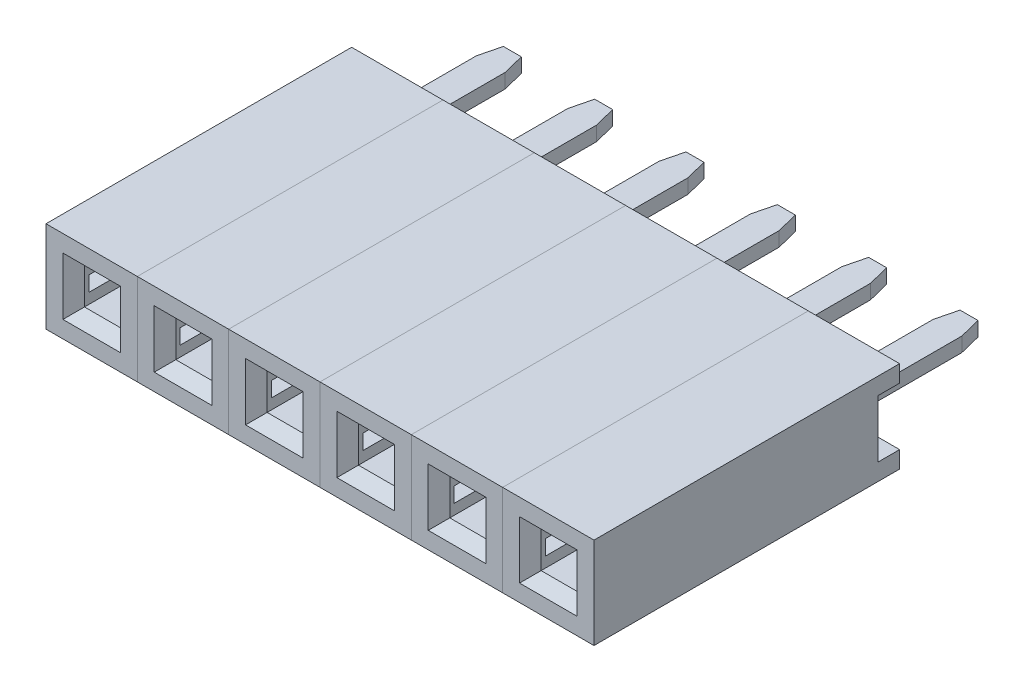
SolidWorks part; units mm, degrees
ref_plane "Спереди" through (0, 0, 0) normal (0, 0, 1) x (1, 0, 0)
ref_plane "Сверху" through (0, 0, 0) normal (0, 1, 0) x (1, 0, 0)
ref_plane "Справа" through (0, 0, 0) normal (1, 0, 0) x (0, 0, -1)
sketch "Эскиз1" plane through (0, 0, 0) normal (0, 0, 1) x (1, 0, 0)
  line L0 (0, 1.27) -> (0, 0) construction
  line L1 (1.27, 2.54) -> (-1.27, 2.54)
  line L2 (1.27, 2.54) -> (1.27, 0)
  line L3 (1.27, 0) -> (-1.27, 0)
  line L4 (-1.27, 2.54) -> (-1.27, 0)
  line L5 (1.27, 2.54) -> (-1.27, 0) construction
  line L6 (1.27, 0) -> (-1.27, 2.54) construction
  dimension "D1" = 2.54
extrude "Бобышка-Вытянуть1" add sketch "Эскиз1" along normal blind 8.5
sketch "Эскиз2" plane through (0, 0, 0) normal (0, 0, -1) x (-1, 0, 0)
  line L0 (0, 1.27) -> (0, 0) construction
  line L1 (1, 1.48) -> (-1, 1.48)
  line L2 (1, 1.48) -> (1, 1.06)
  line L3 (1, 1.06) -> (-1, 1.06)
  line L4 (-1, 1.48) -> (-1, 1.06)
  line L5 (1, 1.48) -> (-1, 1.06) construction
  line L6 (1, 1.06) -> (-1, 1.48) construction
  line L7 (0, 1.27) -> (-1.27, 1.27) construction
  line L8 (-1.27, 0) -> (-1.27, 2.54) construction
  point P0 (0, 1.27)
  dimension "D1" = 2
  dimension "D2" = 0.42
extrude "Вырез-Вытянуть1" cut sketch "Эскиз2" against normal offset from surface (8.08 mm away) 0.42 up to face at (0, 1.27, 8.5)
sketch "Эскиз3" plane through (0, 0, 8.5) normal (0, 0, 1) x (1, 0, 0)
  line L0 (0, 1.27) -> (-1.27, 1.27) construction
  line L1 (-0.5, 0.77) -> (0.5, 0.77)
  line L2 (-0.5, 0.77) -> (-0.5, 1.77)
  line L3 (-0.5, 1.77) -> (0.5, 1.77)
  line L4 (0.5, 0.77) -> (0.5, 1.77)
  line L5 (-0.5, 0.77) -> (0.5, 1.77) construction
  line L6 (-0.5, 1.77) -> (0.5, 0.77) construction
  line L7 (-1.27, 2.54) -> (-1.27, 0) construction
  line L8 (0, 1.27) -> (0, 0) construction
  line L9 (-1.27, 0) -> (1.27, 0) construction
  point P0 (0, 1.27)
  dimension "D1" = 1
  dimension "D2" = 1
extrude "Вырез-Вытянуть2" cut sketch "Эскиз3" against normal offset from surface (6.5 mm away) 2 up to face at (0, 1.27, 0)
sketch "Эскиз4" plane through (-1.27, 0, 0) normal (-1, 0, 0) x (0, 0, 1)
  line L0 (0, 2.54) -> (0, 0) construction
  line L1 (0.6, 0.47) -> (0, 0.47)
  line L2 (0.6, 0.47) -> (0.6, 2.07)
  line L3 (0.6, 2.07) -> (0, 2.07)
  line L4 (0, 0.47) -> (0, 2.07)
  line L5 (0.6, 0.47) -> (0, 2.07) construction
  line L6 (0.6, 2.07) -> (0, 0.47) construction
  line L7 (0.3, 1.27) -> (0, 1.27) construction
  point P0 (0.3, 1.27)
  dimension "D1" = 0.6
  dimension "D2" = 1.6
extrude "Вырез-Вытянуть3" cut sketch "Эскиз4" against normal through all
ref_plane "Плоскость1" through (0, 1.27, 0) normal (0, -1, 0) x (-1, 0, 0)
sketch "Эскиз6" plane through (0, 1.27, 0) normal (0, -1, 0) x (-1, 0, 0)
  line L1 (-1, -8.08) -> (-1, -0.6) construction
  line L2 (1, -8.08) -> (1, -0.6) construction
  line L4 (-1.27, 0) -> (1.27, 0) construction
  line L10 (-1, -0.6) -> (1, -0.6) construction
  line L18 (-0.4, 0) -> (0.4, 0)
  line L19 (-0.6, -0.6) -> (-0.4, -0.6)
  line L20 (-1, -2.6) -> (-1, -0.85)
  line L21 (1, -2.6) -> (1, -0.85)
  line L22 (-0.4, -0.6) -> (-0.4, 0)
  line L23 (0.4, -0.6) -> (0.4, 0)
  line L24 (0, 0) -> (0, -0.6) construction
  line L25 (-1, -2.6) -> (-0.8133, -6.1)
  line L26 (-0.8133, -6.1) -> (-0.45, -6.75)
  line L27 (-0.45, -6.75) -> (-0.3, -6.35)
  line L28 (-0.3, -6.35) -> (-0.5, -2.6)
  line L29 (-0.5, -2.6) -> (-0.5, -1.7)
  line L30 (-0.5, -1.7) -> (0, -1.7) construction
  line L31 (0.5, -1.7) -> (0.5, -2.6)
  line L32 (0.5, -2.6) -> (0.3, -6.35)
  line L33 (0.3, -6.35) -> (0.45, -6.75)
  line L34 (0.45, -6.75) -> (0.8133, -6.1)
  line L35 (0.8133, -6.1) -> (1, -2.6)
  line L36 (-1, -2.6) -> (-0.5, -2.6) construction
  line L37 (0.5, -2.6) -> (-0.5, -2.6) construction
  line L38 (1, -2.6) -> (0.5, -2.6) construction
  line L39 (-0.3, -6.35) -> (0.3, -6.35) construction
  line L40 (-0.45, -6.75) -> (0.45, -6.75) construction
  line L41 (-0.8133, -6.1) -> (0.8133, -6.1) construction
  line L42 (0, -1.7) -> (0.5, -1.7) construction
  line L43 (0, -1.7) -> (0, -0.6) construction
  line L44 (-1, -0.85) -> (-0.6, -0.6)
  line L45 (1, -0.85) -> (0.6, -0.6)
  line L46 (-1, -0.85) -> (1, -0.85) construction
  line L47 (0.4, -0.6) -> (0.6, -0.6)
  arc A0 (-0.5, -1.7) -> (0.5, -1.7) centre (0, -1.7) cw
  dimension "D1" = 0.8
  dimension "D2" = 0.6
  dimension "D3" = 1
  dimension "D4" = 1.2
  dimension "D5" = 0.25
  dimension "D6" = 1.1
  dimension "D7" = 2
  dimension "D8" = 0.4
  dimension "D9" = 0.25
  dimension "D10" = 3.5
  dimension "D11" = 0.9
  dimension "D12" = 1.2
extrude "Бобышка-Вытянуть2" add sketch "Эскиз6" along normal mid plane 0.4 separate body contours L29 A0 L31 L32 L33 L34 L35 L21 L45 L19 L44 L20 L25 L26 L27 L28 | L19 L23 L18 L22
chamfer "Фаска1" distance 0.3 angle 45 4 edges at (0, 0.77, 8.5) (0.5, 1.27, 8.5) (0, 1.77, 8.5) (-0.5, 1.27, 8.5)
sketch "Sketch1" plane through (0, 0, 0) normal (0, 0, -1) x (-1, 0, 0)
  line L1 (-0.4, 1.47) -> (0.4, 1.47)
  line L2 (-0.4, 1.47) -> (-0.4, 1.07)
  line L3 (-0.4, 1.07) -> (0.4, 1.07)
  line L4 (0.4, 1.47) -> (0.4, 1.07)
extrude "Boss-Extrude1" add sketch "Sketch1" along normal blind 3.2
sketch "Sketch2" plane through (0, 1.47, 0) normal (0, 1, 0) x (1, 0, 0)
  line L0 (-0.4, 2.6) -> (0.4, 2.6) construction
  line L1 (-0.4, -0.6) -> (-0.4, 3.2) construction
  line L2 (0.4, -0.6) -> (0.4, 3.2) construction
  line L3 (-0.4, 3.2) -> (0.4, 3.2) construction
  line L4 (0, 3.2) -> (0, 2.6) construction
  line L5 (-0.25, 3.2) -> (-0.25, 2.6) construction
  line L6 (-0.25, 3.2) -> (-0.4, 2.6)
  line L7 (-0.4, 2.6) -> (-0.5333, 2.6)
  line L8 (-0.5333, 2.6) -> (-0.5333, 3.3233)
  line L9 (-0.5333, 3.3233) -> (-0.25, 3.3233)
  line L10 (-0.25, 3.3233) -> (-0.25, 3.2)
  line L11 (-0.25, 3.2) -> (-0.2501, 3.2095)
  line L12 (0.4, 2.6) -> (0.5333, 2.6)
  line L13 (0.25, 3.2) -> (0.4, 2.6)
  line L14 (0.25, 3.3233) -> (0.25, 3.2)
  line L15 (0.5333, 2.6) -> (0.5333, 3.3233)
  line L16 (0.5333, 3.3233) -> (0.25, 3.3233)
  dimension "D1" = 0.6
  dimension "D2" = 0.25
extrude "Cut-Extrude1" cut sketch "Sketch2" against normal blind 1
pattern_linear "LPattern1" count 6 spacing 2.54 along (1, 0, 0) of bodies 127
